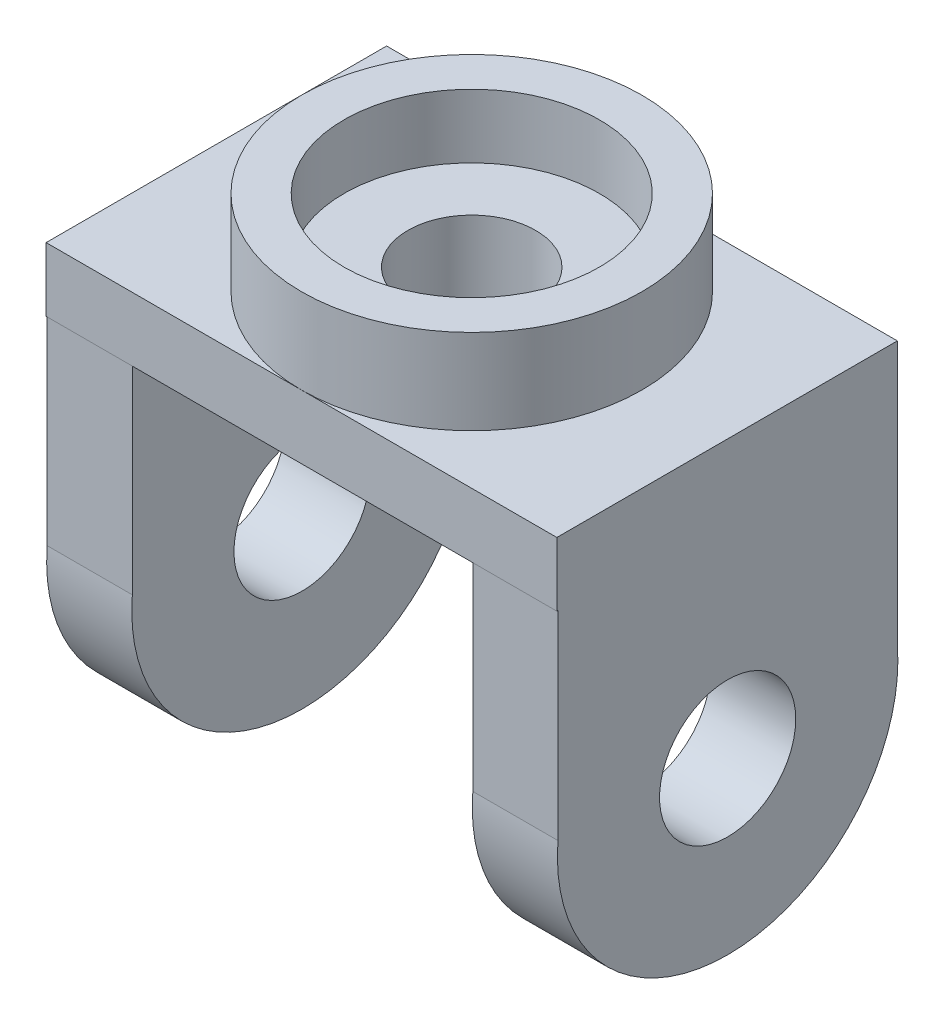
SolidWorks part; units mm, degrees
ref_plane "Front Plane" through (0, 0, 0) normal (0, 0, 1) x (1, 0, 0)
ref_plane "Top Plane" through (0, 0, 0) normal (0, 1, 0) x (1, 0, 0)
ref_plane "Right Plane" through (0, 0, 0) normal (1, 0, 0) x (0, 0, -1)
sketch "Sketch1" plane through (0, 0, 0) normal (0, 1, 0) x (1, 0, 0)
  line L1 (-60, 40) -> (60, 40)
  line L2 (-60, 40) -> (-60, -40)
  line L3 (-60, -40) -> (60, -40)
  line L4 (60, 40) -> (60, -40)
  line L5 (-60, 40) -> (60, -40) construction
  line L6 (-60, -40) -> (60, 40) construction
  point P0 (0, 0)
  dimension "D1" = 120
  dimension "D2" = 80
extrude "Boss-Extrude1" add sketch "Sketch1" along normal blind 15
sketch "Sketch2" plane through (0, 15, 0) normal (0, 1, 0) x (1, 0, 0)
  circle A0 centre (0, 0) radius 40
  dimension "D1" = 80
extrude "Boss-Extrude2" add sketch "Sketch2" along normal blind 20
sketch "Sketch3" plane through (0, 35, 0) normal (0, 1, 0) x (1, 0, 0)
  circle A0 centre (0, 0) radius 30
  dimension "D1" = 60
extrude "Cut-Extrude1" cut sketch "Sketch3" against normal blind 15
sketch "Sketch4" plane through (0, 20, 0) normal (0, 1, 0) x (1, 0, 0)
  circle A0 centre (0, 0) radius 15
  dimension "D1" = 30
extrude "Cut-Extrude2" cut sketch "Sketch4" against normal through all
sketch "Sketch5" plane through (60, 0, 0) normal (1, 0, 0) x (0, 0, -1)
  line L1 (40, 0) -> (-39.744, 0)
  line L2 (40, 0) -> (40, -50)
  line L3 (40, -50) -> (-39.744, -50)
  line L4 (-39.744, 0) -> (-39.744, -50)
  circle A0 centre (0.128, -50) radius 40
  line M3 (-40, 0) -> (40, 0)
  dimension "D2" = 80
  dimension "D1" = 50
extrude "Boss-Extrude3" add sketch "Sketch5" against normal blind 20 contours A0 L2 L4 M3 | L2 A0 L4 L3 | L4 A0 L2 L3
sketch "Sketch6" plane through (60, 0, 0) normal (1, 0, 0) x (0, 0, -1)
  circle A0 centre (0.128, -50) radius 16
  dimension "D1" = 32
extrude "Cut-Extrude3" cut sketch "Sketch6" against normal through all
mirror "Mirror2" about plane through (0, 0, 0) normal (1, 0, 0) of "Cut-Extrude3", "Boss-Extrude3"
